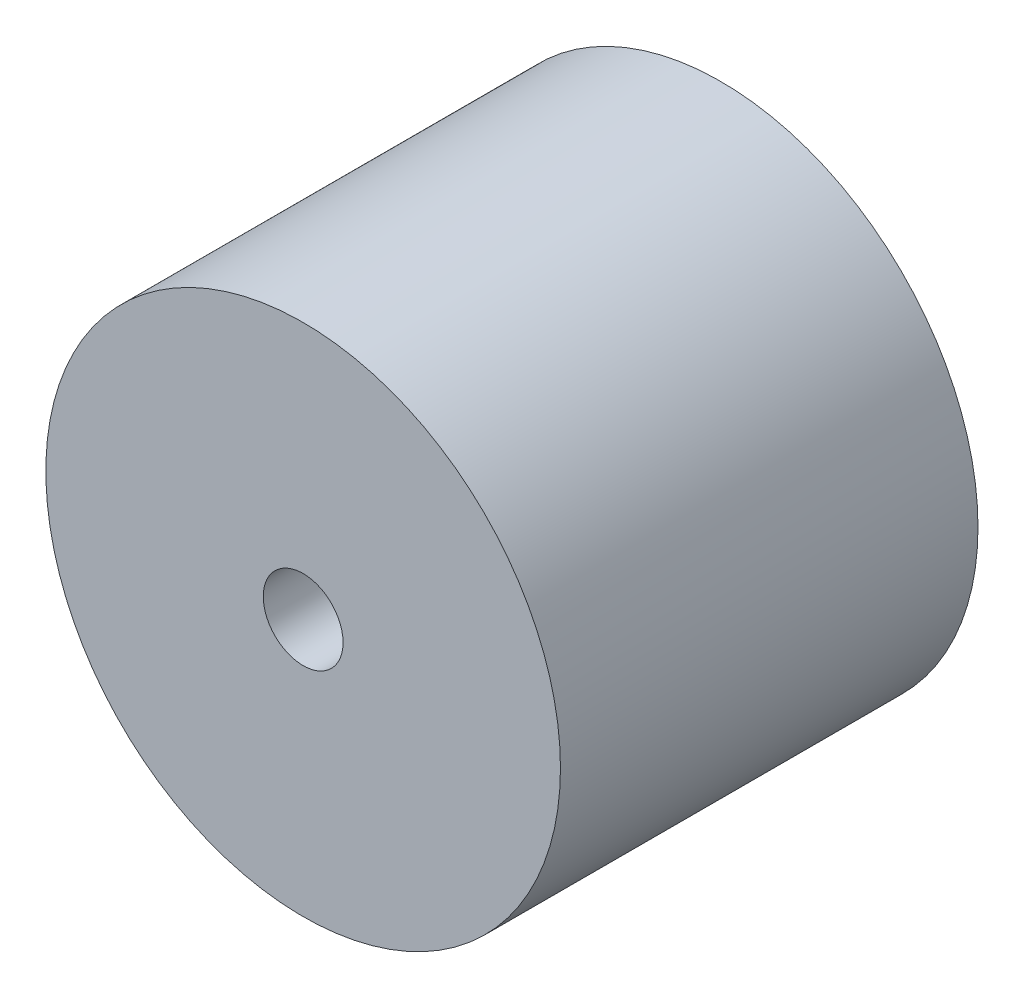
SolidWorks part; units mm, degrees
ref_plane "Front Plane" through (0, 0, 0) normal (0, 0, 1) x (1, 0, 0)
ref_plane "Top Plane" through (0, 0, 0) normal (0, 1, 0) x (1, 0, 0)
ref_plane "Right Plane" through (0, 0, 0) normal (1, 0, 0) x (0, 0, -1)
sketch "Sketch2" plane through (0, 0, 0) normal (0, 0, 1) x (1, 0, 0)
  circle A0 centre (0, 0) radius 26.5
  circle A1 centre (0, 0) radius 4.11
  dimension "D1" = 53
  dimension "D2" = 8.22
extrude "Boss-Extrude1" add sketch "Sketch2" along normal blind 43
